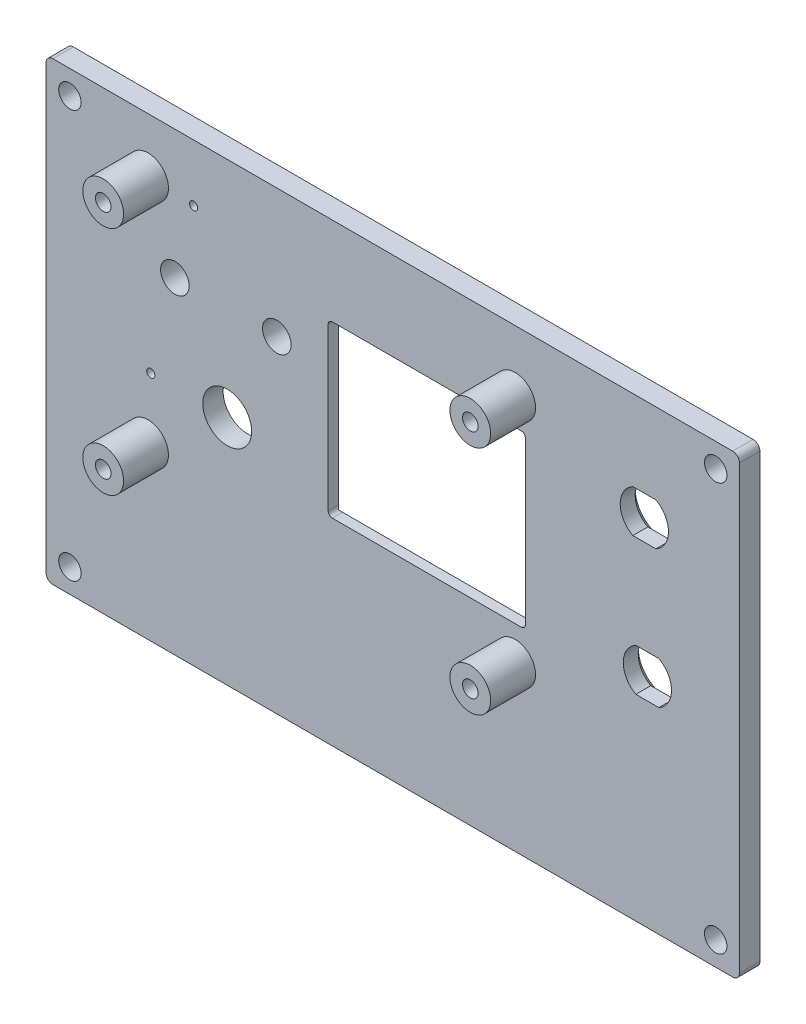
SolidWorks part; units mm, degrees
ref_plane "前视基准面" through (0, 0, 0) normal (0, 0, 1) x (1, 0, 0)
ref_plane "上视基准面" through (0, 0, 0) normal (0, 1, 0) x (1, 0, 0)
ref_plane "右视基准面" through (0, 0, 0) normal (1, 0, 0) x (0, 0, -1)
other "Configuration Table"
sketch "草图1" plane through (0, 0, 0) normal (0, 0, 1) x (1, 0, 0)
  line L1 (0, 0) -> (102, 0)
  line L2 (0, 0) -> (0, 67)
  line L3 (0, 67) -> (102, 67)
  line L4 (102, 0) -> (102, 67)
  dimension "D1" = 102
  dimension "D2" = 67
extrude "凸台-拉伸1" add sketch "草图1" along normal blind 3
fillet "圆角1" radius 1 4 edges at (102, 67, 1.5) (102, 0, 1.5) (0, 67, 1.5) (0, 0, 1.5)
sketch "草图2" plane through (0, 0, 3) normal (0, 0, 1) x (1, 0, 0)
  line L0 (101, 67) -> (1, 67) construction
  line L1 (0, 66) -> (0, 1) construction
  circle A0 centre (15, 59) radius 3
  circle A1 centre (15, 59) radius 1.15
  circle A2 centre (15, 25) radius 3
  circle A3 centre (15, 25) radius 1.15
  circle A6 centre (69, 24.0243) radius 3
  circle A7 centre (69, 24.0243) radius 1.15
  circle A8 centre (69, 58.0243) radius 3
  circle A9 centre (69, 58.0243) radius 1.15
  dimension "D1" = 6
  dimension "D2" = 2.3
  dimension "D5" = 6
  dimension "D6" = 2.3
  dimension "D9" = 6
  dimension "2.3" = 2.3
  dimension "D11" = 6
  dimension "D12" = 2.3
  dimension "D3" = 8
  dimension "D4" = 15
  dimension "D13" = 54
  dimension "D14" = 34
  dimension "D15" = 34
  dimension "D16" = 54
extrude "凸台-拉伸2" add sketch "草图2" along normal blind 6.6
sketch "草图3" plane through (0, 0, 3) normal (0, 0, 1) x (1, 0, 0)
  line L0 (86.7573, 35.1443) -> (90.1444, 35.1443)
  line L1 (41.5, 54.0243) -> (70.5, 54.0243)
  line L2 (41.5, 54.0243) -> (41.5, 29.0243)
  line L3 (41.5, 29.0243) -> (70.5, 29.0243)
  line L4 (70.5, 54.0243) -> (70.5, 29.0243)
  line L5 (86.3065, 55.1443) -> (89.6935, 55.1443)
  line L7 (86.3065, 48.9043) -> (89.6935, 48.9043)
  line L9 (86.7573, 28.9043) -> (90.1444, 28.9043)
  arc A0 (89.6935, 48.9043) -> (89.6935, 55.1443) centre (88, 52.0243) ccw
  circle A1 centre (69, 58.0243) radius 1.15 construction
  circle A2 centre (69, 24.0243) radius 1.15 construction
  circle A3 centre (69, 58.0243) radius 1.15 construction
  circle A4 centre (26.64, 34.12) radius 3.6
  circle A5 centre (15, 25) radius 1.15 construction
  circle A6 centre (15, 25) radius 1.15 construction
  circle A7 centre (18.94, 48.06) radius 2.1
  circle A8 centre (33.94, 48.06) radius 2.1
  circle A9 centre (15, 59) radius 1.15 construction
  arc A10 (86.3065, 55.1443) -> (86.3065, 48.9043) centre (88, 52.0243) ccw
  arc A11 (90.1444, 28.9043) -> (90.1444, 35.1443) centre (88.4509, 32.0243) ccw
  arc A12 (86.7573, 35.1443) -> (86.7573, 28.9043) centre (88.4509, 32.0243) ccw
  circle A13 centre (21.7, 58.6) radius 0.6
  circle A14 centre (15.4, 34.13) radius 0.6
  dimension "D1" = 4
  dimension "D7" = 7.2
  dimension "D11" = 4.2
  dimension "D12" = 4.2
  dimension "D13" = 7.1
  dimension "D16" = 7.1
  dimension "D24" = 1.2
  dimension "D25" = 24.87
  dimension "D27" = 1.2
  dimension "D2" = 5
  dimension "D3" = 1.5
  dimension "D4" = 29
  dimension "D5" = 9.12
  dimension "D6" = 11.64
  dimension "D8" = 3.94
  dimension "D9" = 10.94
  dimension "D10" = 15
  dimension "D14" = 3.12
  dimension "D15" = 3.12
  dimension "D17" = 3.12
  dimension "D18" = 3.12
  dimension "D19" = 19
  dimension "D20" = 6
  dimension "D21" = 20
  dimension "D22" = 6.7
  dimension "D23" = 0.4
  dimension "D26" = 0.4
extrude "切除-拉伸1" cut sketch "草图3" against normal through all
chamfer "倒角1" distance 1.5 angle 45 4 edges at (70.5, 41.5243, 0) (56, 29.0243, 0) (41.5, 41.5243, 0) (56, 54.0243, 0)
chamfer "倒角2" distance 0.8 angle 45 8 edges at (92.0009, 32.0243, 0) (88.4509, 28.9043, 0) (84.9009, 32.0243, 0) (88.4509, 35.1443, 0) (91.55, 52.0243, 0) (88, 48.9043, 0) (84.45, 52.0243, 0) (88, 55.1443, 0)
sketch "草图4" plane through (0, 0, 0) normal (0, 0, -1) x (-1, 0, 0)
  line L0 (-101, 67) -> (-1, 67) construction
  line L1 (-102, 1) -> (-102, 66) construction
  line L2 (0, 66) -> (0, 1) construction
  line L3 (-1, 0) -> (-101, 0) construction
  circle A0 centre (-98.5, 63.5) radius 1.65
  circle A1 centre (-3.5, 63.5) radius 1.65
  circle A2 centre (-3.5, 3.5) radius 1.65
  circle A3 centre (-98.5, 3.5) radius 1.65
  dimension "D1" = 3.3
  dimension "D2" = 3.5
  dimension "D3" = 3.5
  dimension "D4" = 3.5
  dimension "D5" = 3.5
  dimension "D6" = 3.5
extrude "切除-拉伸2" cut sketch "草图4" against normal through all
fillet "圆角2" radius 0.6 4 edges at (70.5, 29.0243, 2.25) (41.5, 29.0243, 2.25) (70.5, 54.0243, 2.25) (41.5, 54.0243, 2.25)
